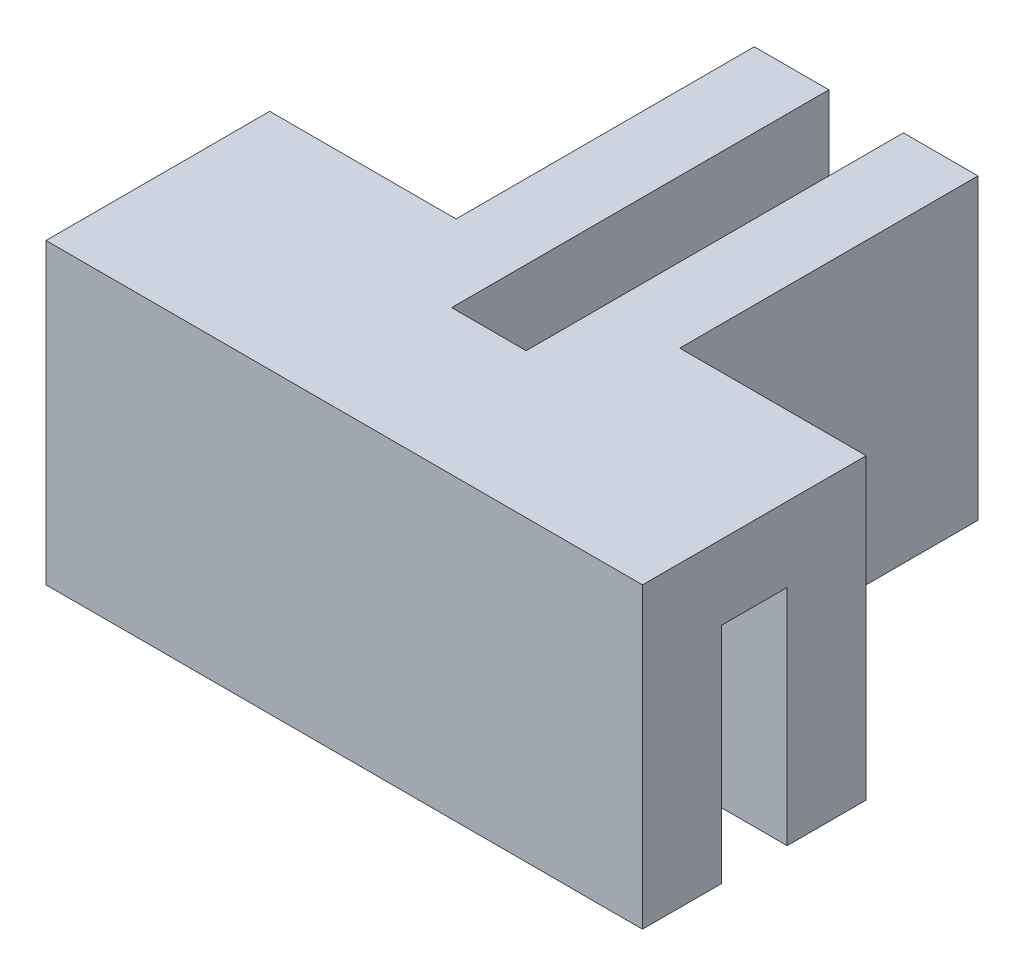
SolidWorks part; units mm, degrees
ref_plane "Front Plane" through (0, 0, 0) normal (0, 0, 1) x (1, 0, 0)
ref_plane "Top Plane" through (0, 0, 0) normal (0, 1, 0) x (1, 0, 0)
ref_plane "Right Plane" through (0, 0, 0) normal (1, 0, 0) x (0, 0, -1)
sketch "Sketch2" plane through (0, 0, 0) normal (0, 1, 0) x (1, 0, 0)
  line L0 (-1.5875, 6.35) -> (1.5875, 6.35) construction
  line L1 (-12.7, 0) -> (12.7, 0)
  line L2 (-12.7, 0) -> (-12.7, -9.525)
  line L3 (-12.7, -9.525) -> (12.7, -9.525)
  line L4 (12.7, 0) -> (12.7, -9.525)
  line L5 (-4.7625, 0) -> (-1.5875, 0)
  line L6 (-4.7625, 0) -> (-4.7625, 12.7)
  line L7 (-4.7625, 12.7) -> (-1.5875, 12.7)
  line L8 (-1.5875, 0) -> (-1.5875, 12.7)
  line L9 (4.7625, 0) -> (1.5875, 0)
  line L10 (4.7625, 0) -> (4.7625, 12.7)
  line L11 (4.7625, 12.7) -> (1.5875, 12.7)
  line L12 (1.5875, 0) -> (1.5875, 12.7)
  line L13 (-12.7, -3.3655) -> (12.7, -3.3655) construction
  line L14 (-1.5875, 0) -> (1.5875, 0)
  line L15 (-1.5875, 0) -> (-1.5875, -3.3655)
  line L16 (-1.5875, -3.3655) -> (1.5875, -3.3655)
  line L17 (1.5875, 0) -> (1.5875, -3.3655)
  line L18 (-12.7, -6.1595) -> (12.7, -6.1595) construction
  line L19 (-12.7, -6.1595) -> (-12.7, -3.3655) construction
  point P13 (0, 0)
  point P17 (0, 6.35)
  point P24 (-12.7, -4.7625)
  point P25 (-12.7, -4.7625)
  dimension "D1" = 3.175
  dimension "D2" = 9.525
  dimension "D3" = 25.4
  dimension "D4" = 3.175
  dimension "D5" = 12.7
  dimension "D6" = 2.794
extrude "Boss-Extrude1" add sketch "Sketch2" along normal blind 12.7 contours L4 L1 L2 L3 | L1 L8 L7 L6 | L12 L1 L10 L11
sketch "Sketch3" plane through (0, 0, 0) normal (0, -1, 0) x (1, 0, 0)
  line L0 (-12.7, 0) -> (-12.7, 9.525) construction
  line L1 (-12.7, 6.1595) -> (12.7, 6.1595)
  line L2 (-12.7, 6.1595) -> (-12.7, 3.3655)
  line L3 (-12.7, 3.3655) -> (12.7, 3.3655)
  line L4 (12.7, 6.1595) -> (12.7, 3.3655)
  line L5 (12.7, 0) -> (12.7, 9.525) construction
  point P12 (-12.7, 4.7625)
  point P13 (-12.7, 4.7625)
  dimension "D1" = 2.794
extrude "Cut-Extrude1" cut sketch "Sketch3" against normal blind 9.525
